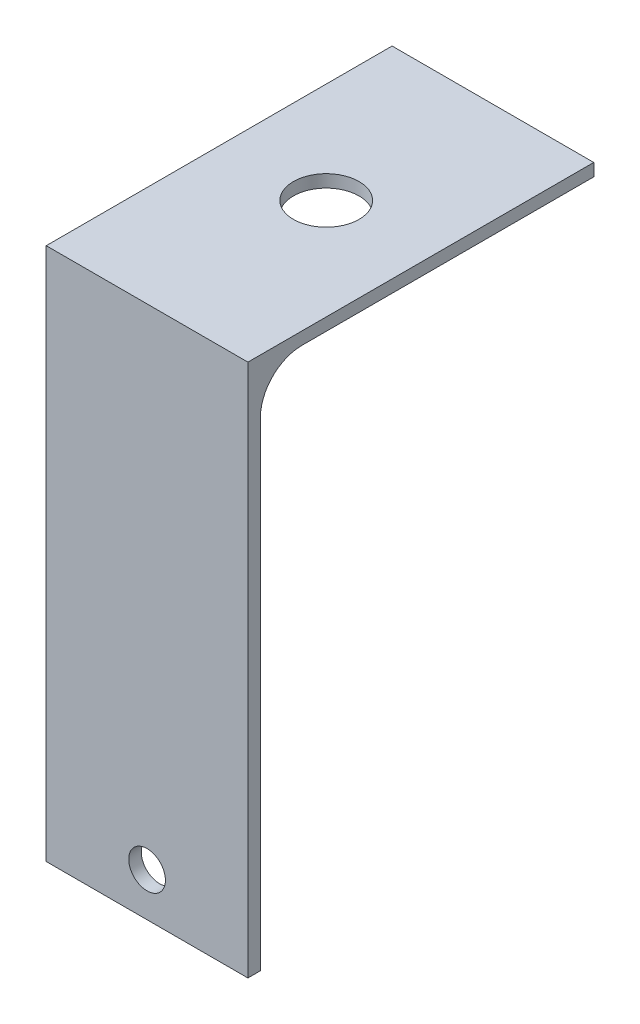
SolidWorks part; units mm, degrees
material "1060 Alloy"
ref_plane "Front Plane" through (0, 0, 0) normal (0, 0, 1) x (1, 0, 0)
ref_plane "Top Plane" through (0, 0, 0) normal (0, 1, 0) x (1, 0, 0)
ref_plane "Right Plane" through (0, 0, 0) normal (1, 0, 0) x (0, 0, -1)
sketch "Sketch1" plane through (0, 0, 0) normal (0, 0, 1) x (1, 0, 0)
  line L1 (12.1, -32) -> (-12.1, -32)
  line L2 (12.1, -32) -> (12.1, 32)
  line L3 (12.1, 32) -> (-12.1, 32)
  line L4 (-12.1, -32) -> (-12.1, 32)
  line L5 (12.1, -32) -> (-12.1, 32) construction
  line L6 (12.1, 32) -> (-12.1, -32) construction
  point P0 (0, 0)
  dimension "Base" = 24.2
  dimension "ServoToTop" = 64
extrude "Boss-Extrude1" add sketch "Sketch1" along normal blind 1.5
sketch "Sketch2" plane through (0, 0, 1.5) normal (0, 0, 1) x (1, 0, 0)
  line L0 (-12.1, -32) -> (12.1, -32) construction
  line L1 (12.1, -32) -> (12.1, 32) construction
  circle A0 centre (0, -26.8) radius 2.2
  dimension "D2" = 4.4
  dimension "D1" = 5.2
  dimension "D3" = 12.1
extrude "Cut-Extrude1" cut sketch "Sketch2" against normal through all
sketch "Sketch4" plane through (0, 32, 0) normal (0, 1, 0) x (1, 0, 0)
  line L0 (-12.1, -1.5) -> (-12.1, 0) construction
  line L1 (-12.1, 0) -> (12.1, 0)
  line L2 (-12.1, 0) -> (-12.1, 40)
  line L3 (-12.1, 40) -> (12.1, 40)
  line L4 (12.1, 0) -> (12.1, 40)
  line L5 (12.1, -1.5) -> (12.1, 0) construction
  dimension "BaseTopLength" = 40
extrude "Boss-Extrude2" add sketch "Sketch4" against normal blind 1.5
sketch "Sketch5" plane through (0, 30.5, 0) normal (0, -1, 0) x (1, 0, 0)
  line L0 (-12.1, 0) -> (12.1, 0) construction
  line L1 (-12.1, -40) -> (-12.1, 0) construction
  circle A0 centre (0, -20) radius 3.937
  dimension "D1" = 7.874
  dimension "D2" = 20
  dimension "D3" = 12.1
extrude "Cut-Extrude2" cut sketch "Sketch5" against normal through all
fillet "Fillet1" radius 5 1 edges at (0, 30.5, 0)
